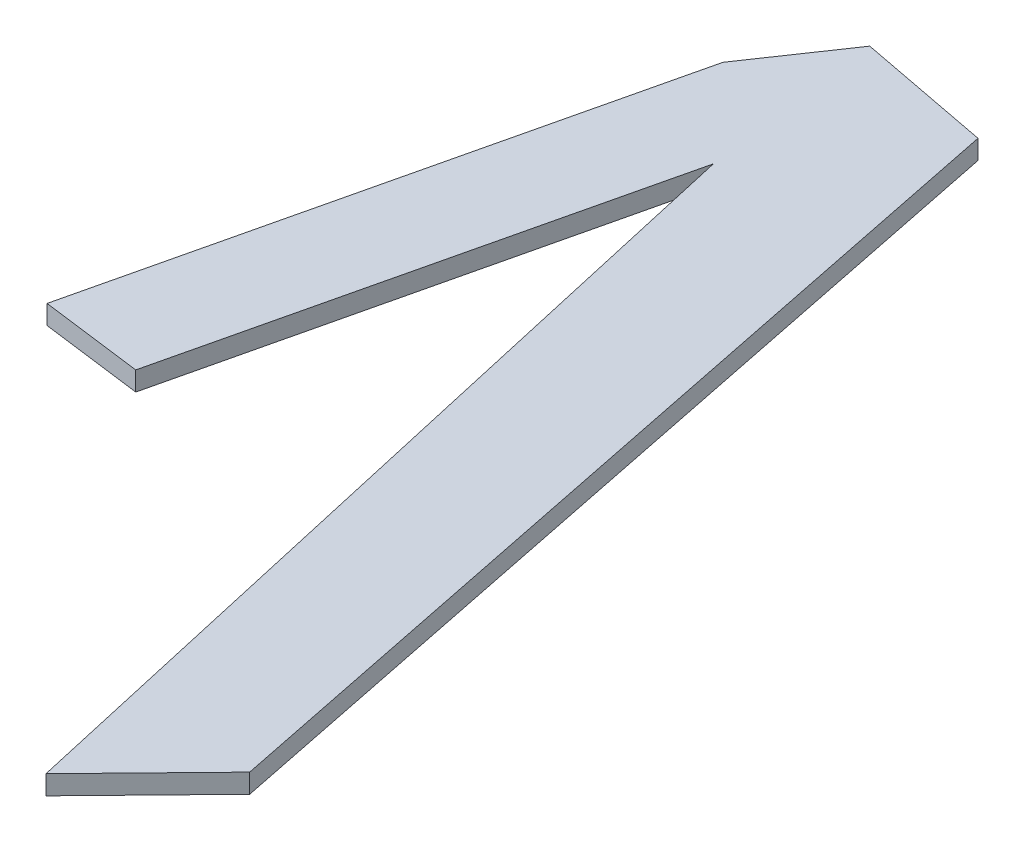
SolidWorks part; units mm, degrees
ref_plane "Front Plane" through (0, 0, 0) normal (0, 0, 1) x (1, 0, 0)
ref_plane "Top Plane" through (0, 0, 0) normal (0, 1, 0) x (1, 0, 0)
ref_plane "Right Plane" through (0, 0, 0) normal (1, 0, 0) x (0, 0, -1)
sketch "Sketch1" plane through (0, 0, 0) normal (0, 1, 0) x (1, 0, 0)
  line L0 (0, 0) -> (-5.7452, -24.3309)
  line L1 (-5.7452, -24.3309) -> (-11.0504, -23.6402)
  line L2 (-11.0504, -23.6402) -> (-4.3285, 4.8269)
  line L3 (-4.3285, 4.8269) -> (-1.236, 9.3752)
  line L4 (-1.236, 9.3752) -> (5.737, 8.0382)
  line L5 (5.737, 8.0382) -> (15.3561, -39.4984)
  line L6 (15.3561, -39.4984) -> (10.1241, -44.8721)
  line L7 (10.1241, -44.8721) -> (0, 0)
  point P3 (0, 0)
  point P10 (-6.45, 5.1226)
  point P11 (0, 10.3351)
  point P12 (5.7517, 6.2011)
  point P13 (0, 10.3351)
  point P14 (-1.2582, 8.358)
  point P15 (0, 0)
  point P16 (0, 0)
  point P17 (0, 9.0528)
  point P18 (6.291, 9.0528)
  point P19 (19.5918, -41.071)
  point P20 (-5.4962, -23.2765)
  point P21 (-3.7746, 5.8416)
  dimension "D1" = 7.1
  dimension "D2" = 5.5
  dimension "D3" = 29.25
  dimension "D4" = 5.35
  dimension "D5" = 25
  dimension "D6" = 26
  dimension "D7" = 46
  dimension "D8" = 7.5
  dimension "D9" = 48.5
extrude "Boss-Extrude1" add sketch "Sketch1" along normal blind 1
